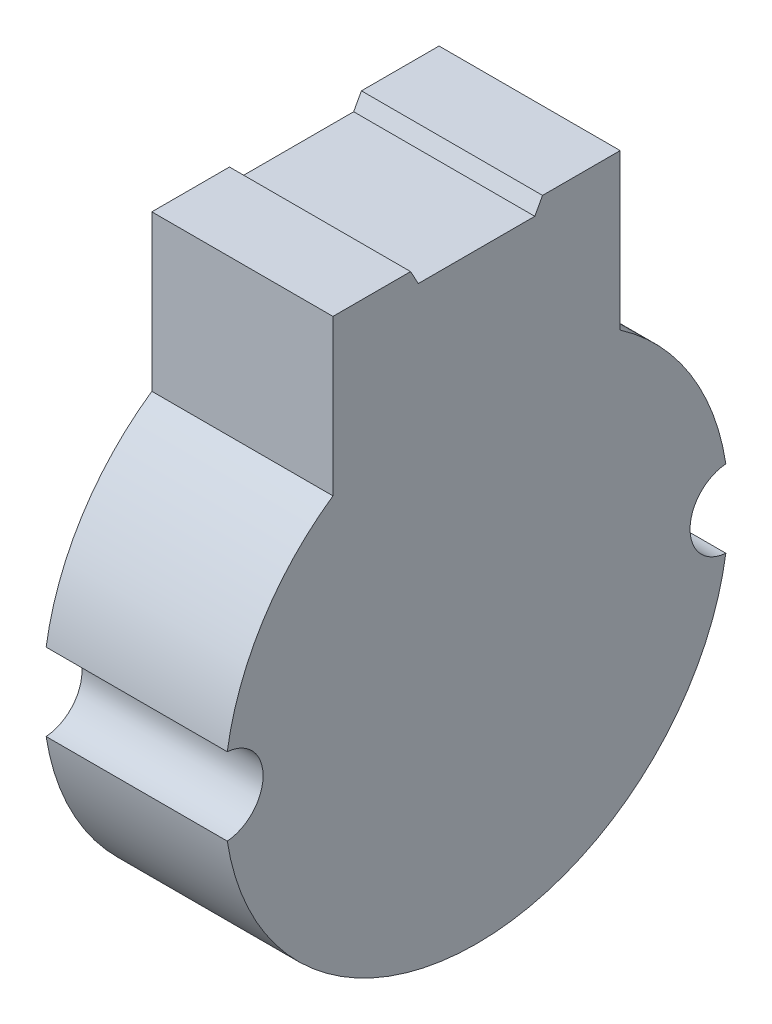
SolidWorks part; units mm, degrees
ref_plane "Front Plane" through (0, 0, 0) normal (0, 0, 1) x (1, 0, 0)
ref_plane "Top Plane" through (0, 0, 0) normal (0, 1, 0) x (1, 0, 0)
ref_plane "Right Plane" through (0, 0, 0) normal (1, 0, 0) x (0, 0, -1)
sketch "Sketch1" plane through (0, 0, 0) normal (1, 0, 0) x (0, 0, -1)
  line L0 (-4.5, 22.6739) -> (4.5, 22.6739)
  line L1 (0, -4.2739) -> (0, 23.6739) construction
  line L2 (-11.1, 11.7586) -> (-11.1, 23.7739)
  line L3 (-11.1, 23.7739) -> (-5.1, 23.7739)
  line L4 (11.1, 23.7739) -> (11.1, 11.7586)
  line L5 (-4.5, 22.6739) -> (-5.1, 23.7739)
  line L6 (4.5, 22.6739) -> (5.1, 23.7739)
  line L7 (5.1, 23.7739) -> (11.1, 23.7739)
  arc A0 (-19.2692, -7.265) -> (19.2692, -7.265) centre (0, -4.2739) ccw
  arc A1 (-19.2692, -7.265) -> (-19.2692, -1.2827) centre (-19.5, -4.2739) ccw
  arc A2 (19.2692, -1.2827) -> (19.2692, -7.265) centre (19.5, -4.2739) ccw
  arc A3 (19.2692, -1.2827) -> (11.1, 11.7586) centre (0, -4.2739) ccw
  arc A4 (-11.1, 11.7586) -> (-19.2692, -1.2827) centre (0, -4.2739) ccw
  point P7 (0, -4.2739)
  point P16 (0, 22.6739)
  dimension "D1" = 6
  dimension "D2" = 4.5
  dimension "D3" = 6
extrude "Boss-Extrude1" add sketch "Sketch1" along normal blind 14
